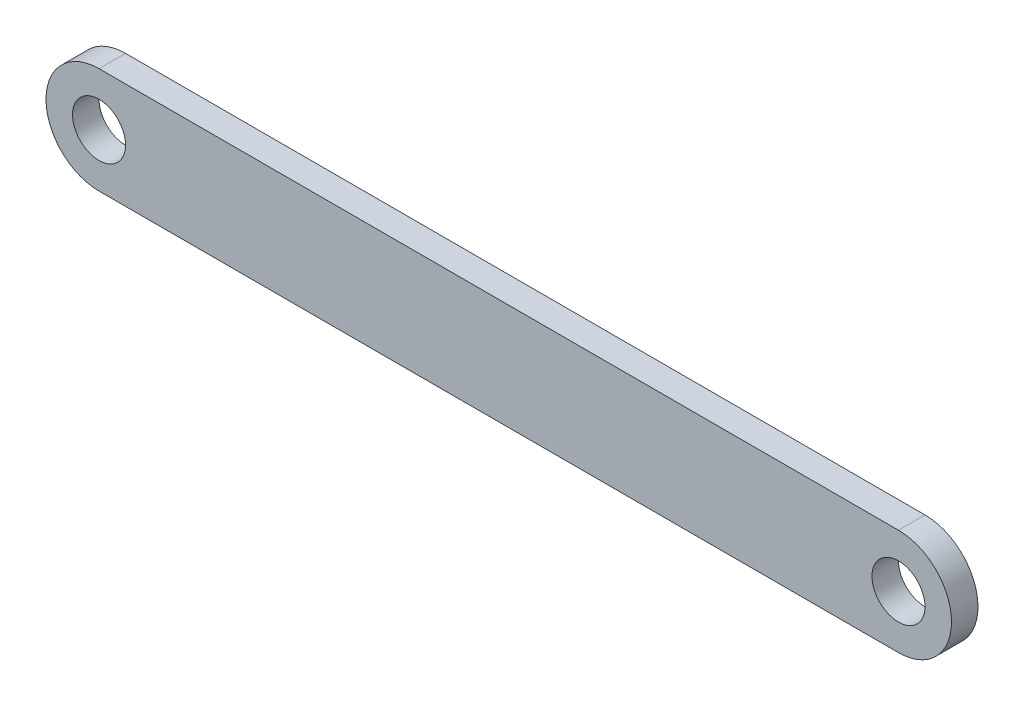
SolidWorks part; units mm, degrees
ref_plane "Спереди" through (0, 0, 0) normal (0, 0, 1) x (1, 0, 0)
ref_plane "Сверху" through (0, 0, 0) normal (0, 1, 0) x (1, 0, 0)
ref_plane "Справа" through (0, 0, 0) normal (1, 0, 0) x (0, 0, -1)
sketch "Эскиз1" plane through (0, 0, 0) normal (0, 0, 1) x (1, 0, 0)
  line L0 (0, 0) -> (-30.1536, 0)
  line L1 (-30.1536, -2) -> (0, -2)
  line L2 (-30.1536, 2) -> (0, 2)
  circle A0 centre (-30.1536, 0) radius 1
  circle A1 centre (0, 0) radius 1
  circle A2 centre (-30.1536, 0) radius 2
  circle A3 centre (0, 0) radius 2
  dimension "D1" = 30.1536
extrude "Бобышка-Вытянуть1" add sketch "Эскиз1" along normal mid plane 1
sketch "Sketch1" plane through (0, 0, 0) normal (0, 0, 1) x (1, 0, 0)
  line L0 (0, 0) -> (-14, 0)
  line L1 (-14, 0) -> (-14, 1.5)
  line L2 (-25.5979, -2) -> (-2.0642, -2)
  line L3 (-14, 0) -> (-30.1536, 0)
  line L7 (-14, 1.5) -> (-20.4712, -4.9712)
  line L11 (0, 2) -> (-30.8022, 2)
  line L12 (-14, 1.5) -> (-7.5288, -4.9712)
  line L13 (-20.4712, -4.9712) -> (-7.5288, -4.9712)
  line L14 (-15.6569, 5.5) -> (-30.1281, -8.9712)
  line L15 (-30.1281, -8.9712) -> (2.1281, -8.9712)
  line L16 (-12.3431, 5.5) -> (2.1281, -8.9712)
  line L17 (-14, 1.5) -> (-14, 5.5)
  line L18 (-14, 5.5) -> (-15.6569, 5.5)
  line L19 (-14, 5.5) -> (-12.3431, 5.5)
  line L21 (-14, 7.1569) -> (-30.1281, -8.9712) construction
  line L22 (-14, 7.1569) -> (2.1281, -8.9712) construction
  point P6 (-9.7278, -2.9956)
  point P9 (-14.7071, 0.7071)
  point P10 (-13.2929, 0.7071)
  point P11 (-21.4142, -2.5858)
  point P15 (-16, 0)
  point P22 (-10, 0)
  dimension "D1" = 4
  dimension "D4" = 14
  dimension "D2" = 1.5
